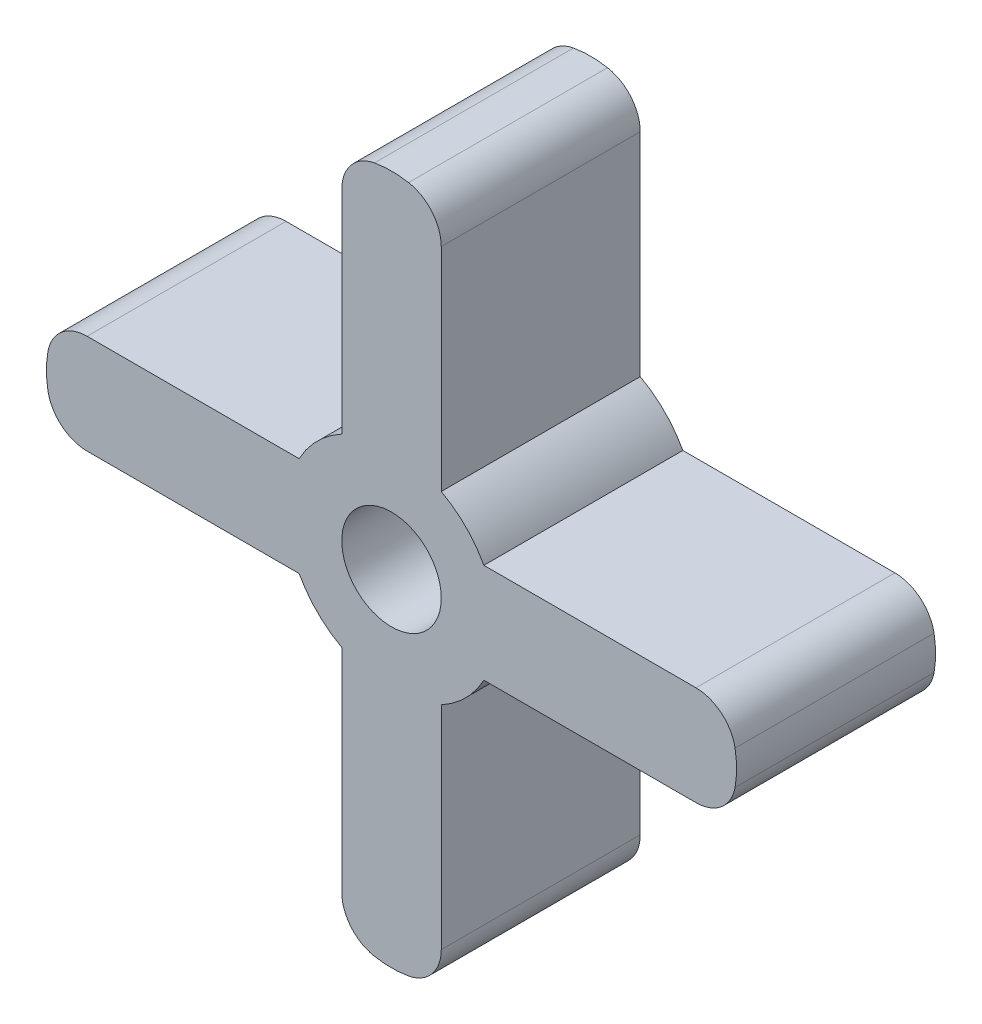
SolidWorks part; units mm, degrees
material "ABS"
ref_plane "Front Plane" through (0, 0, 0) normal (0, 0, 1) x (1, 0, 0)
ref_plane "Top Plane" through (0, 0, 0) normal (0, 1, 0) x (1, 0, 0)
ref_plane "Right Plane" through (0, 0, 0) normal (1, 0, 0) x (0, 0, -1)
sketch "Sketch3" plane through (0, 0, 0) normal (0, 0, 1) x (1, 0, 0)
  line L0 (-2.5, 4.6421) -> (-2.5, 16.6421)
  line L1 (0, 17.3442) -> (0, 5.2725) construction
  line L2 (2.5, 4.6421) -> (2.5, 16.6421)
  line L3 (4.6421, 2.5) -> (16.6421, 2.5)
  line L4 (4.6421, -2.5) -> (16.6421, -2.5)
  line L5 (2.5, -4.6421) -> (2.5, -16.6421)
  line L6 (-2.5, -4.6421) -> (-2.5, -16.6421)
  line L7 (-4.6421, -2.5) -> (-16.6421, -2.5)
  line L8 (-4.6421, 2.5) -> (-16.6421, 2.5)
  line L9 (0, -5.2725) -> (0, -17.3442) construction
  arc A0 (-2.5, 4.6421) -> (-4.6421, 2.5) centre (0, 0) ccw
  arc A1 (-2.5, 16.6421) -> (2.5, 16.6421) centre (0, 12.5423) cw
  arc A2 (16.6421, 2.5) -> (16.6421, -2.5) centre (12.5423, 0) cw
  arc A3 (2.5, -16.6421) -> (-2.5, -16.6421) centre (0, -12.5423) cw
  arc A4 (-16.6421, -2.5) -> (-16.6421, 2.5) centre (-12.5423, 0) cw
  arc A5 (4.6421, 2.5) -> (2.5, 4.6421) centre (0, 0) ccw
  arc A6 (-4.6421, -2.5) -> (-2.5, -4.6421) centre (0, 0) ccw
  arc A7 (2.5, -4.6421) -> (4.6421, -2.5) centre (0, 0) ccw
  point P1 (0, -17.3442)
  point P12 (0, 17.3442)
  point P28 (0, 0)
  dimension "D1" = 5
  dimension "D2" = 20
  dimension "D4" = 12
  dimension "D3" = 4
extrude "Boss-Extrude1" add sketch "Sketch3" along normal blind 10
fillet "Fillet1" radius 2 8 edges at (16.6421, 2.5, 5) (16.6421, -2.5, 5) (2.5, -16.6421, 5) (-2.5, -16.6421, 5) (-16.6421, -2.5, 5) (-16.6421, 2.5, 5) (2.5, 16.6421, 5) (-2.5, 16.6421, 5)
sketch "Sketch4" plane through (0, 0, 0) normal (0, 0, 1) x (1, 0, 0)
  circle A0 centre (0, 0) radius 2.5
extrude "Cut-Extrude1" cut sketch "Sketch4" along normal through all both and the other way through all
